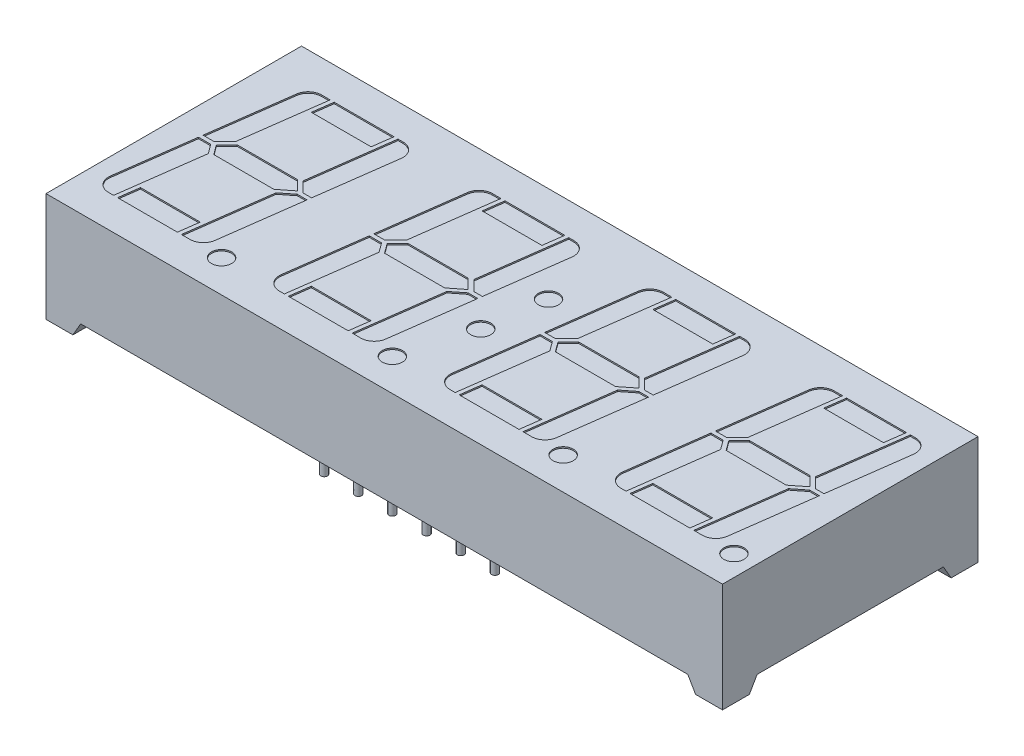
SolidWorks part; units mm, degrees
ref_plane "Спереди" through (0, 0, 0) normal (0, 0, 1) x (1, 0, 0)
ref_plane "Сверху" through (0, 0, 0) normal (0, 1, 0) x (1, 0, 0)
ref_plane "Справа" through (0, 0, 0) normal (1, 0, 0) x (0, 0, -1)
sketch "Эскиз1" plane through (0, 0, 0) normal (0, 1, 0) x (1, 0, 0)
  line L1 (-25.15, 9.5) -> (25.15, 9.5)
  line L2 (-25.15, 9.5) -> (-25.15, -9.5)
  line L3 (-25.15, -9.5) -> (25.15, -9.5)
  line L4 (25.15, 9.5) -> (25.15, -9.5)
  line L5 (-25.15, 9.5) -> (25.15, -9.5) construction
  line L6 (-25.15, -9.5) -> (25.15, 9.5) construction
  point P0 (0, 0)
  dimension "D1" = 50.3
  dimension "D2" = 19
extrude "Бобышка-Вытянуть1" add sketch "Эскиз1" along normal blind 8.1
sketch "Эскиз2" plane through (0, 8.1, 0) normal (0, 1, 0) x (1, 0, 0)
  line L0 (-25.15, 0) -> (25.15, 0) construction
  line L1 (-25.15, 9.5) -> (-25.15, -9.5) construction
  line L2 (25.15, -9.5) -> (25.15, 9.5) construction
  line L3 (-22.1321, 7.1) -> (-24.0398, -7.1)
  line L4 (-24.0398, -7.1) -> (-15.9679, -7.1)
  line L5 (-15.9679, -7.1) -> (-14.0602, 7.1)
  line L6 (-14.0602, 7.1) -> (-22.1321, 7.1)
  line L7 (-22.1321, 7.1) -> (-15.9679, -7.1) construction
  line L8 (-24.0398, -7.1) -> (-14.0602, 7.1) construction
  line L9 (-20.8201, 5.6) -> (-22.3248, -5.6)
  line L10 (-22.3248, -5.6) -> (-17.2799, -5.6)
  line L11 (-17.2799, -5.6) -> (-15.7752, 5.6)
  line L12 (-15.7752, 5.6) -> (-20.8201, 5.6)
  line L13 (-22.9852, 0.75) -> (-14.9133, 0.75)
  line L14 (-12.3276, 9.0288) -> (-14.6913, -8.5653) construction
  line L15 (-23.1867, -0.75) -> (-15.1148, -0.75)
  line L16 (-9.4321, 7.1) -> (-11.3398, -7.1)
  line L17 (-11.3398, -7.1) -> (-3.2679, -7.1)
  line L18 (-3.2679, -7.1) -> (-1.3602, 7.1)
  line L19 (-1.3602, 7.1) -> (-9.4321, 7.1)
  line L20 (-8.1201, 5.6) -> (-9.6248, -5.6)
  line L21 (-9.6248, -5.6) -> (-4.5799, -5.6)
  line L22 (-4.5799, -5.6) -> (-3.0752, 5.6)
  line L23 (-3.0752, 5.6) -> (-8.1201, 5.6)
  line L24 (-10.2852, 0.75) -> (-2.2133, 0.75)
  line L25 (-10.4867, -0.75) -> (-2.4148, -0.75)
  line L26 (-9.4321, 7.1) -> (-3.2679, -7.1) construction
  line L27 (-11.3398, -7.1) -> (-1.3602, 7.1) construction
  line L28 (3.2679, 7.1) -> (1.3602, -7.1)
  line L29 (1.3602, -7.1) -> (9.4321, -7.1)
  line L30 (9.4321, -7.1) -> (11.3398, 7.1)
  line L31 (11.3398, 7.1) -> (3.2679, 7.1)
  line L32 (4.5799, 5.6) -> (3.0752, -5.6)
  line L33 (3.0752, -5.6) -> (8.1201, -5.6)
  line L34 (8.1201, -5.6) -> (9.6248, 5.6)
  line L35 (9.6248, 5.6) -> (4.5799, 5.6)
  line L36 (2.4148, 0.75) -> (10.4867, 0.75)
  line L37 (2.2133, -0.75) -> (10.2852, -0.75)
  line L38 (3.2679, 7.1) -> (9.4321, -7.1) construction
  line L39 (1.3602, -7.1) -> (11.3398, 7.1) construction
  line L40 (15.9679, 7.1) -> (14.0602, -7.1)
  line L41 (14.0602, -7.1) -> (22.1321, -7.1)
  line L42 (22.1321, -7.1) -> (24.0398, 7.1)
  line L43 (24.0398, 7.1) -> (15.9679, 7.1)
  line L44 (17.2799, 5.6) -> (15.7752, -5.6)
  line L45 (15.7752, -5.6) -> (20.8201, -5.6)
  line L46 (20.8201, -5.6) -> (22.3248, 5.6)
  line L47 (22.3248, 5.6) -> (17.2799, 5.6)
  line L48 (15.1148, 0.75) -> (23.1867, 0.75)
  line L49 (14.9133, -0.75) -> (22.9852, -0.75)
  line L50 (15.9679, 7.1) -> (22.1321, -7.1) construction
  line L51 (14.0602, -7.1) -> (24.0398, 7.1) construction
  line L53 (-15.0141, 0) -> (-10.3859, 0)
  line L54 (-15.9679, -7.1) -> (-11.3398, -7.1) construction
  line L55 (1.1221, 8.3522) -> (-1.1221, -8.3522) construction
  point P8 (-15.0141, 0)
  point P11 (-19.05, 0)
  point P21 (0, 0)
  point P29 (-6.35, 0)
  point P42 (6.35, 0)
  point P55 (19.05, 0)
  dimension "D1" = 14.2
  dimension "D2" = 8
  dimension "D4" = 1.5
  dimension "D5" = 19.05
  dimension "D7" = 12.7
  dimension "D3" = 1.5
  dimension "D6" = 4
sketch "Эскиз3" plane through (0, 8.1, 0) normal (0, 1, 0) x (1, 0, 0)
  line L6 (-15.0141, 0) -> (-15.6768, 0) construction
  line L7 (-15.6768, 0) -> (-16.4268, 0.75) construction
  line L8 (-16.6283, -0.75) -> (-15.6768, 0) construction
  line L9 (-15.9679, -7.1) -> (-14.0602, 7.1) construction
  line L10 (-23.1128, -0.2) -> (-22.1993, -0.2)
  line L11 (-21.9591, -0.0203) -> (-21.1889, 0.75)
  line L12 (-17.2799, -5.6) -> (-15.7752, 5.6) construction
  line L13 (-21.4254, -0.75) -> (-21.9591, -0.0203)
  line L14 (-20.8201, 5.6) -> (-22.3248, -5.6) construction
  line L15 (-14.0602, 7.1) -> (-22.1321, 7.1) construction
  line L16 (-20.5201, 5.6) -> (-20.3186, 7.1)
  line L17 (-20.5201, 5.6) -> (-16.0752, 5.6)
  line L18 (-20.3186, 7.1) -> (-15.8737, 7.1)
  line L19 (-16.0752, 5.6) -> (-15.8737, 7.1)
  line L20 (-15.7752, 5.6) -> (-20.8201, 5.6) construction
  line L21 (-22.2263, -7.1) -> (-22.0248, -5.6)
  line L22 (-22.2263, -7.1) -> (-17.7814, -7.1)
  line L23 (-22.0248, -5.6) -> (-17.5799, -5.6)
  line L24 (-17.7814, -7.1) -> (-17.5799, -5.6)
  line L25 (-24.0398, -7.1) -> (-15.9679, -7.1) construction
  line L26 (-22.3248, -5.6) -> (-17.2799, -5.6) construction
  line L27 (-23.0859, 0) -> (-22.2217, 0) construction
  line L28 (-22.1321, 7.1) -> (-24.0398, -7.1) construction
  line L29 (-25.15, 0) -> (25.15, 0) construction
  line L30 (-22.2217, 0) -> (-21.4717, 0.75) construction
  line L33 (-23.1867, -0.75) -> (-15.1148, -0.75) construction
  line L34 (-21.6732, -0.75) -> (-22.2217, 0) construction
  line L35 (-22.9852, 0.75) -> (-14.9133, 0.75) construction
  line L36 (-15.0006, 0.1) -> (-15.6354, 0.1)
  line L37 (-15.0409, -0.2) -> (-15.6768, -0.2)
  line L38 (-15.6354, 0.1) -> (-16.41, 0.8747)
  line L39 (-23.0725, 0.1) -> (-22.2631, 0.1)
  line L40 (-22.2631, 0.1) -> (-21.5424, 0.8207)
  line L41 (-21.6924, -0.8931) -> (-22.1993, -0.2)
  line L42 (-15.9774, 0.0177) -> (-16.5682, 0.6086)
  line L43 (-16.6474, -0.8924) -> (-15.769, -0.2)
  line L44 (-16.9538, -0.7519) -> (-15.9774, 0.0177)
  line L45 (-23.0859, -0.2) -> (-22.2217, -0.2) construction
  line L46 (-21.7539, -0.809) -> (-22.3024, -0.059) construction
  line L47 (-23.0859, 0.1) -> (-22.2217, 0.1) construction
  line L48 (-22.2924, 0.0707) -> (-21.5424, 0.8207) construction
  line L49 (-22.0803, -0.1414) -> (-21.3303, 0.6086) construction
  line L50 (-21.5118, -0.6319) -> (-22.0603, 0.1181) construction
  line L51 (-21.5424, 0.8207) -> (-21.4498, 0.9134)
  line L52 (-16.5664, -0.8285) -> (-15.6149, -0.0785) construction
  line L53 (-16.7521, -0.5929) -> (-15.8006, 0.1571) construction
  line L54 (-15.8182, -0.1414) -> (-16.5682, 0.6086) construction
  line L55 (-15.6061, 0.0707) -> (-16.3561, 0.8207) construction
  line L56 (-15.0141, 0.1) -> (-15.6768, 0.1) construction
  line L57 (-15.0141, -0.2) -> (-15.6768, -0.2) construction
  line L58 (-15.6768, -0.2) -> (-15.769, -0.2)
  line L59 (-16.5682, 0.6086) -> (-16.7096, 0.75)
  line L60 (-16.41, 0.8747) -> (-15.5737, 7.1)
  line L61 (-15.5737, 7.1) -> (-15.2035, 7.1)
  line L62 (-14.2124, 5.9668) -> (-15.0006, 0.1)
  line L63 (-16.6474, -0.8924) -> (-17.4814, -7.1)
  line L64 (-17.4814, -7.1) -> (-16.8426, -7.1)
  line L65 (-15.8515, -6.2332) -> (-15.0409, -0.2)
  line L66 (-23.1128, -0.2) -> (-23.8876, -5.9668)
  line L67 (-22.8965, -7.1) -> (-22.5263, -7.1)
  line L68 (-22.5263, -7.1) -> (-21.6924, -0.8931)
  line L69 (-22.2485, 6.2332) -> (-23.0725, 0.1)
  line L70 (-21.2574, 7.1) -> (-20.6186, 7.1)
  line L71 (-20.6186, 7.1) -> (-21.4498, 0.9134)
  line L72 (-21.1889, 0.75) -> (-16.7096, 0.75)
  line L73 (-21.4254, -0.75) -> (-16.9538, -0.7519)
  line L76 (-15.9679, -7.1) -> (-11.3398, -7.1) construction
  line L77 (-12.3276, 9.0288) -> (-14.6913, -8.5653) construction
  arc A0 (-15.2035, 7.1) -> (-14.2124, 5.9668) centre (-15.2035, 6.1) cw
  arc A1 (-16.8426, -7.1) -> (-15.8515, -6.2332) centre (-16.8426, -6.1) ccw
  arc A2 (-23.8876, -5.9668) -> (-22.8965, -7.1) centre (-22.8965, -6.1) ccw
  arc A3 (-22.2485, 6.2332) -> (-21.2574, 7.1) centre (-21.2574, 6.1) cw
  circle A4 centre (-14.4944, -7.1) radius 0.75
  point P69 (-14.0602, 7.1)
  point P87 (-15.9679, -7.1)
  point P90 (-24.0398, -7.1)
  point P96 (-22.1321, 7.1)
  dimension "D11" = 1
  dimension "D12" = 1
  dimension "D1" = 0.3
  dimension "D2" = 0.3
  dimension "D3" = 0.2
  dimension "D5" = 0.1
  dimension "D4" = 0.1
  dimension "D6" = 0.2
  dimension "D7" = 0.1
  dimension "D8" = 0.2
  dimension "D9" = 0.1
  dimension "D10" = 0.2
extrude "Вырез-Вытянуть1" cut sketch "Эскиз3" against normal blind 0.1
sketch "Эскиз4" plane through (0, 8.1, 0) normal (0, 1, 0) x (1, 0, 0)
  line L0 (1.1221, 8.3522) -> (-1.1221, -8.3522) construction
  circle A0 centre (0.3214, 2.3926) radius 0.75
  circle A1 centre (-0.2752, -2.0484) radius 0.75
pattern_linear "Линейный массив1" count 4 spacing 12.7 along (1, 0, 0) of "Вырез-Вытянуть1"
extrude "Вырез-Вытянуть3" cut sketch "Эскиз4" against normal up to surface (0.1 mm away) up to face at (-2.5964, 8, -3.5777)
sketch "Эскиз5" plane through (0, 0, 9.5) normal (0, 0, 1) x (1, 0, 0)
  line L0 (-23.15, 0) -> (-22.5726, 1)
  line L1 (-25.15, 0) -> (25.15, 0) construction
  line L2 (-22.5726, 1) -> (22.5726, 1)
  line L3 (0, -5.215) -> (0, 11.9692) construction
  line L4 (-25.15, 8.1) -> (-25.15, 0) construction
  line L5 (23.15, 0) -> (22.5726, 1)
  line L6 (-23.15, 0) -> (23.15, 0)
  point P12 (0, 1)
  dimension "D1" = 1
  dimension "D2" = 2
extrude "Вырез-Вытянуть4" cut sketch "Эскиз5" against normal through all
sketch "Эскиз6" plane through (25.15, 0, 0) normal (1, 0, 0) x (0, 0, -1)
  line L0 (-7.5, 0) -> (-6.9226, 1)
  line L1 (-9.5, 0) -> (9.5, 0) construction
  line L2 (-6.9226, 1) -> (6.9226, 1)
  line L3 (0, 1) -> (0, 0) construction
  line L4 (7.5, 0) -> (-7.5, 0)
  line L5 (7.5, 0) -> (6.9226, 1)
  line L6 (-9.5, 8.1) -> (-9.5, 0) construction
  dimension "D1" = 1
  dimension "D2" = 2
extrude "Вырез-Вытянуть5" cut sketch "Эскиз6" against normal through all
sketch "Эскиз8" plane through (0, 1, 0) normal (0, -1, 0) x (1, 0, 0)
  line L0 (0, -13.5292) -> (0, 9.1799) construction
  line L1 (8.338, 7.62) -> (-33.1788, 7.62) construction
  line L2 (14.2811, 0) -> (-40.9713, 0) construction
  line L3 (8.1696, -7.62) -> (-32.5724, -7.62) construction
  circle A0 centre (-1.27, -7.62) radius 0.25
  circle A1 centre (-3.81, -7.62) radius 0.25
  circle A2 centre (-6.35, -7.62) radius 0.25
  circle A3 centre (6.35, -7.62) radius 0.25
  circle A4 centre (3.81, -7.62) radius 0.25
  circle A5 centre (1.27, -7.62) radius 0.25
  circle A6 centre (1.27, 7.62) radius 0.25
  circle A7 centre (3.81, 7.62) radius 0.25
  circle A8 centre (6.35, 7.62) radius 0.25
  circle A9 centre (-6.35, 7.62) radius 0.25
  circle A10 centre (-3.81, 7.62) radius 0.25
  circle A11 centre (-1.27, 7.62) radius 0.25
  dimension "D3" = 0.5
  dimension "D1" = 15.24
  dimension "D2" = 7.62
  dimension "D4" = 2.54
  dimension "D5" = 2.54
  dimension "D6" = 1.27
extrude "Бобышка-Вытянуть2" add sketch "Эскиз8" along normal blind 2.5 separate body
